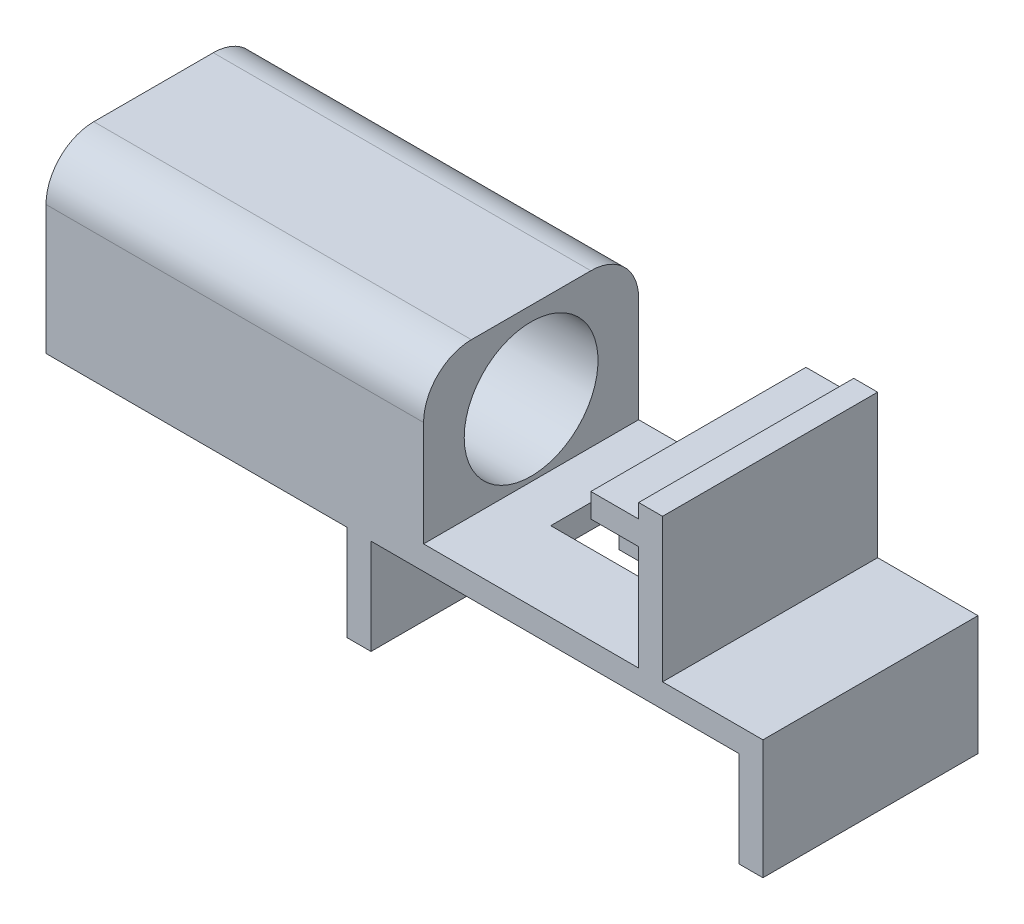
SolidWorks part; units mm, degrees
ref_plane "Front Plane" through (0, 0, 0) normal (0, 0, 1) x (1, 0, 0)
ref_plane "Top Plane" through (0, 0, 0) normal (0, 1, 0) x (1, 0, 0)
ref_plane "Right Plane" through (0, 0, 0) normal (1, 0, 0) x (0, 0, -1)
sketch "Sketch1" plane through (0, 0, 0) normal (0, 1, 0) x (1, 0, 0)
  line L1 (75, -22.5) -> (-75, -22.5)
  line L2 (75, -22.5) -> (75, 22.5)
  line L3 (75, 22.5) -> (-75, 22.5)
  line L4 (-75, -22.5) -> (-75, 22.5)
  line L5 (75, -22.5) -> (-75, 22.5) construction
  line L6 (75, 22.5) -> (-75, -22.5) construction
  point P0 (0, 0)
  dimension "D1" = 150
  dimension "D2" = 45
extrude "Boss-Extrude1" add sketch "Sketch1" along normal blind 5
sketch "Sketch2" plane through (0, 0, 0) normal (0, -1, 0) x (1, 0, 0)
  line L0 (-75, 22.5) -> (75, 22.5) construction
  line L1 (75, -22.5) -> (70, -22.5)
  line L2 (75, -22.5) -> (75, 22.5)
  line L3 (75, 22.5) -> (70, 22.5)
  line L4 (70, -22.5) -> (70, 22.5)
  dimension "D1" = 5
extrude "Boss-Extrude2" add sketch "Sketch2" along normal blind 20
sketch "Sketch3" plane through (0, 0, 0) normal (0, -1, 0) x (1, 0, 0)
  line L0 (70, -22.5) -> (-75, -22.5) construction
  line L1 (-7, -22.5) -> (-12, -22.5)
  line L2 (-7, -22.5) -> (-7, 22.5)
  line L3 (-7, 22.5) -> (-12, 22.5)
  line L4 (-12, -22.5) -> (-12, 22.5)
  line L5 (-75, 22.5) -> (70, 22.5) construction
  line L6 (70, 22.5) -> (70, -22.5) construction
  dimension "D1" = 5
  dimension "D2" = 77
extrude "Boss-Extrude3" add sketch "Sketch3" along normal blind 20
sketch "Sketch4" plane through (0, 0, 0) normal (0, -1, 0) x (1, 0, 0)
  line L0 (70, 22.5) -> (70, -22.5) construction
  line L1 (49, -5.9) -> (14, -5.9)
  line L2 (49, -5.9) -> (49, 5.9)
  line L3 (49, 5.9) -> (14, 5.9)
  line L4 (14, -5.9) -> (14, 5.9)
  line L5 (49, -5.9) -> (14, 5.9) construction
  line L6 (49, 5.9) -> (14, -5.9) construction
  line L7 (30.25, 0) -> (-30.25, 0) construction
  point P0 (31.5, 0)
  dimension "D1" = 35
  dimension "D2" = 21
  dimension "D3" = 11.8
extrude "Cut-Extrude1" cut sketch "Sketch4" against normal through all
sketch "Sketch5" plane through (0, 0, 0) normal (0, -1, 0) x (1, 0, 0)
  line L0 (14, -5.9) -> (49, -5.9) construction
  line L1 (16.5, -5.9) -> (46.5, -5.9)
  line L2 (16.5, -5.9) -> (16.5, -8.9)
  line L3 (16.5, -8.9) -> (46.5, -8.9)
  line L4 (46.5, -5.9) -> (46.5, -8.9)
  point P7 (31.5, -5.9)
  dimension "D1" = 3
  dimension "D2" = 30
extrude "Boss-Extrude4" add sketch "Sketch5" along normal blind 4
mirror "Mirror1" about plane through (0, 0, 0) normal (0, 0, 1) of "Boss-Extrude4"
sketch "Sketch7" plane through (0, 5, 0) normal (0, 1, 0) x (1, 0, 0)
  line L0 (49, 5.9) -> (49, -5.9) construction
  line L1 (49, 22.5) -> (54, 22.5)
  line L2 (49, 22.5) -> (49, -22.5)
  line L3 (49, -22.5) -> (54, -22.5)
  line L4 (54, 22.5) -> (54, -22.5)
  line L5 (-75, -22.5) -> (75, -22.5) construction
  point P4 (49, 0)
  dimension "D1" = 5
extrude "Boss-Extrude5" add sketch "Sketch7" along normal blind 30
sketch "Sketch8" plane through (0, 5, 0) normal (0, 1, 0) x (1, 0, 0)
  line L0 (-75, -22.5) -> (49, -22.5) construction
  line L1 (-75, 22.5) -> (4, 22.5)
  line L2 (-75, 22.5) -> (-75, -22.5)
  line L3 (-75, -22.5) -> (4, -22.5)
  line L4 (4, 22.5) -> (4, -22.5)
  line L5 (14, -5.9) -> (14, 5.9) construction
  dimension "D1" = 10
extrude "Boss-Extrude6" add sketch "Sketch8" along normal blind 32
sketch "Sketch9" plane through (-75, 0, 0) normal (-1, 0, 0) x (0, 0, 1)
  line L0 (-22.5, 0) -> (22.5, 0) construction
  circle A0 centre (0, 20) radius 14
  dimension "D1" = 28
  dimension "D2" = 20
extrude "Cut-Extrude2" cut sketch "Sketch9" against normal up to next contours A0
fillet "Fillet1" radius 10
sketch "Sketch10" plane through (49, 0, 0) normal (-1, 0, 0) x (0, 0, 1)
  line L0 (22.5, 35) -> (22.5, 5) construction
  line L1 (22.5, 32) -> (-22.5, 32)
  line L2 (22.5, 32) -> (22.5, 27)
  line L3 (22.5, 27) -> (-22.5, 27)
  line L4 (-22.5, 32) -> (-22.5, 27)
  line L5 (-22.5, 35) -> (-22.5, 5) construction
  line L6 (-22.5, 35) -> (22.5, 35) construction
  dimension "D1" = 5
  dimension "D2" = 3
extrude "Boss-Extrude7" add sketch "Sketch10" along normal blind 10
sketch "Sketch11" plane through (0, 0, 0) normal (0, -1, 0) x (1, 0, 0)
  line L0 (-75, -22.5) -> (-75, 22.5) construction
  circle A0 centre (-60, 0) radius 2.55
  point P4 (-75, 0)
  dimension "D1" = 5.1
  dimension "D2" = 15
extrude "Cut-Extrude3" cut sketch "Sketch11" against normal up to next
sketch "Sketch12" plane through (0, 0, 0) normal (0, -1, 0) x (1, 0, 0)
  line L1 (-55.95, -2.3383) -> (-55.95, 2.3383)
  line L2 (-55.95, 2.3383) -> (-60, 4.6765)
  line L3 (-60, 4.6765) -> (-64.05, 2.3383)
  line L4 (-64.05, 2.3383) -> (-64.05, -2.3383)
  line L5 (-64.05, -2.3383) -> (-60, -4.6765)
  line L6 (-60, -4.6765) -> (-55.95, -2.3383)
  circle A0 centre (-60, 0) radius 4.05 construction
  dimension "D1" = 8.1
extrude "Cut-Extrude4" cut sketch "Sketch12" against normal blind 4
pattern_linear "LPattern1" count 2 spacing 30 along (1, 0, 0) of "Cut-Extrude3", "Cut-Extrude4"
